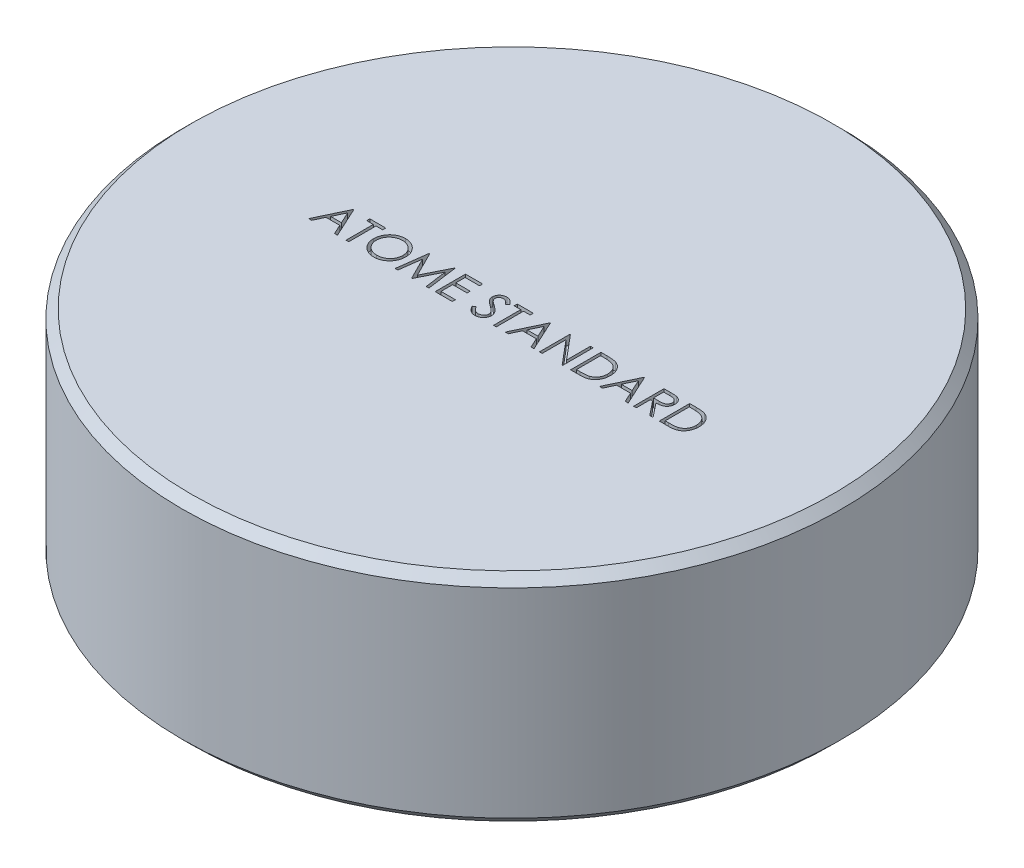
SolidWorks part; units mm, degrees
ref_plane "Plan de face" through (0, 0, 0) normal (0, 0, 1) x (1, 0, 0)
ref_plane "Plan de dessus" through (0, 0, 0) normal (0, 1, 0) x (1, 0, 0)
ref_plane "Plan de droite" through (0, 0, 0) normal (1, 0, 0) x (0, 0, -1)
sketch "Esquisse1" plane through (0, 0, 0) normal (0, 1, 0) x (1, 0, 0)
  circle A0 centre (0, 0) radius 38
  dimension "D1" = 76
extrude "Boss.-Extru.1" add sketch "Esquisse1" along normal blind 25
chamfer "Chanfrein1" distance 1 angle 45 1 edges at (0, 25, 38)
chamfer "Chanfrein2" distance 1 angle 45 1 edges at (0, 0, 38)
sketch "Esquisse2" plane through (0, 25, 0) normal (0, 1, 0) x (1, 0, 0)
  text T0 "ATOME STANDARD"
extrude "Enlèv. mat.-Extru.1" cut sketch "Esquisse2" against normal blind 1
sketch "Esquisse3" plane through (0, 0, 0) normal (0, -1, 0) x (1, 0, 0)
  text T0 "ATOME STANDARD"
extrude "Enlèv. mat.-Extru.2" cut sketch "Esquisse3" against normal blind 1
